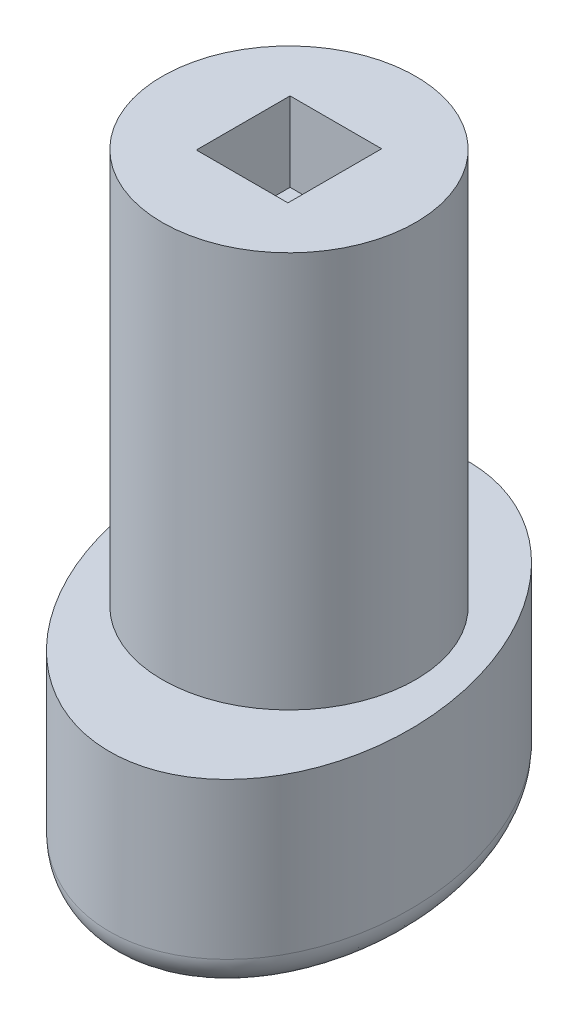
SolidWorks part; units mm, degrees
ref_plane "Front Plane" through (0, 0, 0) normal (0, 0, 1) x (1, 0, 0)
ref_plane "Top Plane" through (0, 0, 0) normal (0, 1, 0) x (1, 0, 0)
ref_plane "Right Plane" through (0, 0, 0) normal (1, 0, 0) x (0, 0, -1)
sketch "Sketch1" plane through (0, 0, 0) normal (0, 1, 0) x (1, 0, 0)
  ellipse E0 centre (0, 0) end of major axis (-1.2101, 3.3438) minor radius 2.54
extrude "Boss-Extrude1" add sketch "Sketch1" along normal blind 3
sketch "Sketch2" plane through (0, 3, 0) normal (0, 1, 0) x (1, 0, 0)
  circle A0 centre (0, 0) radius 2.032
extrude "Boss-Extrude2" add sketch "Sketch2" along normal blind 6.35
sketch "Sketch3" plane through (0, 9.35, 0) normal (0, 1, 0) x (1, 0, 0)
  line L1 (-0.7344, -0.7516) -> (0.7344, -0.7516)
  line L2 (-0.7344, -0.7516) -> (-0.7344, 0.7516)
  line L3 (-0.7344, 0.7516) -> (0.7344, 0.7516)
  line L4 (0.7344, -0.7516) -> (0.7344, 0.7516)
  line L5 (-0.7344, -0.7516) -> (0.7344, 0.7516) construction
  line L6 (-0.7344, 0.7516) -> (0.7344, -0.7516) construction
  point P0 (0, 0)
extrude "Cut-Extrude1" cut sketch "Sketch3" against normal blind 1.27
fillet "Fillet1" radius 0.5 1 edges at (-1.2101, 0, -3.3438)
